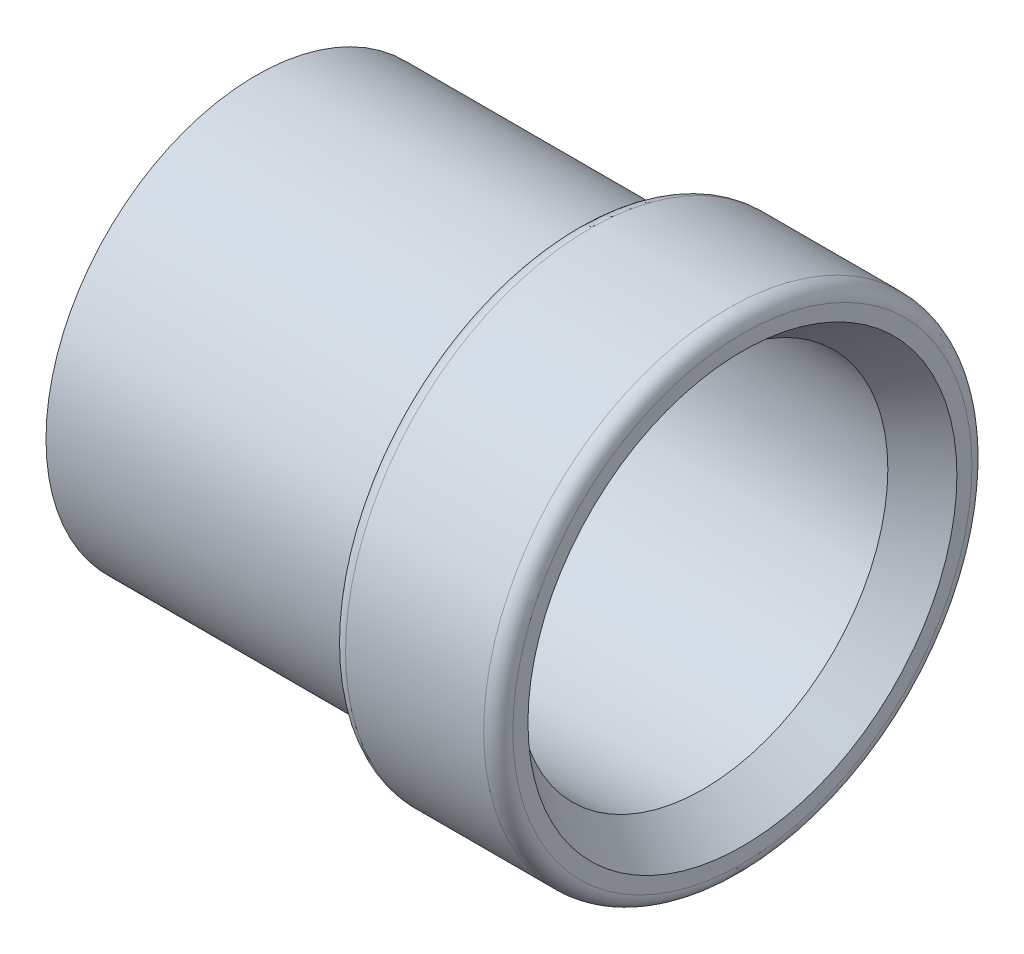
SolidWorks part; units mm, degrees
ref_plane "Front Plane" through (0, 0, 0) normal (0, 0, 1) x (1, 0, 0)
ref_plane "Top Plane" through (0, 0, 0) normal (0, 1, 0) x (1, 0, 0)
ref_plane "Right Plane" through (0, 0, 0) normal (1, 0, 0) x (0, 0, -1)
sketch "Sketch1" plane through (0, 0, 0) normal (0, 0, 1) x (1, 0, 0)
  line L0 (-6.35, 0) -> (6.35, 0) construction
  line L1 (-6.35, 4.826) -> (5.3219, 4.826)
  line L2 (5.3219, 4.826) -> (6.35, 5.6007)
  line L4 (6.35, 5.6007) -> (6.35, 5.9944)
  line L5 (5.969, 6.3754) -> (2.3622, 6.3754)
  line L6 (1.9812, 5.9944) -> (1.9812, 5.4864)
  line L7 (1.9812, 5.4864) -> (-6.35, 5.4864)
  line L8 (-6.35, 4.826) -> (-6.35, 5.4864)
  arc A0 (6.35, 5.9944) -> (5.969, 6.3754) centre (5.969, 5.9944) ccw
  arc A1 (2.3622, 6.3754) -> (1.9812, 5.9944) centre (2.3622, 5.9944) ccw
  point P12 (6.35, 6.3754)
  point P15 (1.9812, 6.3754)
  dimension "D2" = 0.381
  dimension "D1" = 37
  dimension "M" = 12.7
  dimension "G" = 12.7508
  dimension "J" = 4.3688
  dimension "B" = 9.652
  dimension "C" = 10.9728
  dimension "F" = 11.2014
revolve "Revolve1" add sketch "Sketch1" angle 360 about L0
